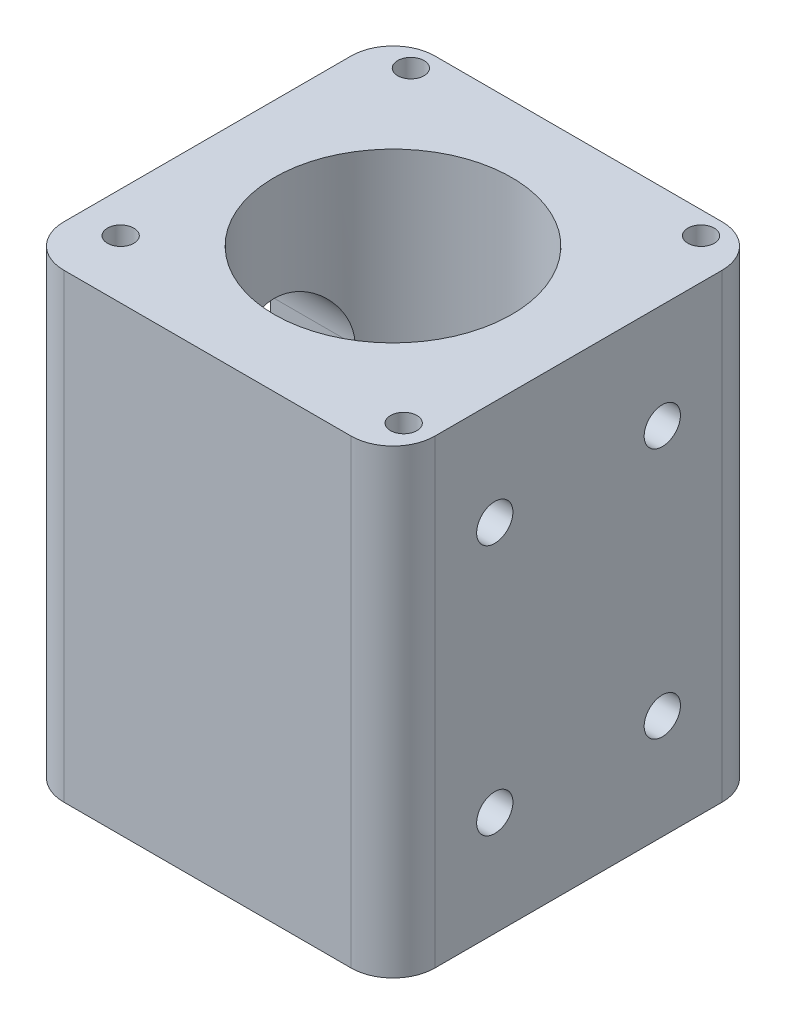
SolidWorks part; units mm, degrees
ref_plane "Front Plane" through (0, 0, 0) normal (0, 0, 1) x (1, 0, 0)
ref_plane "Top Plane" through (0, 0, 0) normal (0, 1, 0) x (1, 0, 0)
ref_plane "Right Plane" through (0, 0, 0) normal (1, 0, 0) x (0, 0, -1)
ref_plane "Plane1"
sketch "Sketch1" plane through (0, 0, 0) normal (0, 1, 0) x (-1, 0, 0)
  line L0 (28.1305, 28.1305) -> (-28.1305, 28.1305)
  line L1 (-28.1305, 28.1305) -> (-28.1305, -28.1305)
  line L2 (-28.1305, -28.1305) -> (28.1305, -28.1305)
  line L3 (28.1305, -28.1305) -> (28.1305, 28.1305)
  dimension "D1" = 56.261
  dimension "D2" = 56.261
extrude "Extrusion1" add sketch "Sketch1" along normal blind 69.85
hole_wizard "Hole1" positions "Sketch3" profile "Sketch2" legacy
sketch "Sketch3" plane through (0, 69.85, 0) normal (0, 1, 0) x (1, 0, 0)
  point P1 (-22, 24.7091)
  point P2 (22, 24.7091)
  point P3 (24.0589, -22.4333)
  point P4 (-22, -19.2909)
sketch "Sketch2" plane through (-22, 69.85, -24.7091) normal (1, 0, 0) x (0, 0, 1)
  line L0 (0, 0) -> (0, 26.6017)
  line L1 (0, 26.6017) -> (2, 25.4)
  line L2 (2, 25.4) -> (2, 0)
  line L4 (2, 0) -> (0, 0)
  line L6 (0, 26.6017) -> (-2, 25.4) construction
  line L7 (0, -4.2442) -> (0, 117.3081) construction
  dimension "Diameter" = 4
  dimension "Depth" = 25.4
  dimension "Drill Angle" = 118
sketch "Sketch4" plane through (0, 69.85, 0) normal (0, 1, 0) x (-1, 0, 0)
  circle A0 centre (0, 0) radius 18
  dimension "D1" = 36
extrude "Extrusion2" cut sketch "Sketch4" against normal blind 254
hole_wizard "Hole2" positions "Sketch6" profile "Sketch5" legacy
sketch "Sketch6" plane through (0, 0, 0) normal (0, -1, 0) x (-1, 0, 0)
  point P1 (23.3446, -23.5712)
  point P2 (-23.7978, -23.5712)
  point P3 (-23.7978, 23.5712)
  point P4 (23.3446, 23.5712)
sketch "Sketch5" plane through (-23.3446, 0, 23.5712) normal (1, 0, 0) x (0, 0, -1)
  line L0 (0, 0) -> (0, 26.9022)
  line L1 (0, 26.9022) -> (2.5, 25.4)
  line L2 (2.5, 25.4) -> (2.5, 0)
  line L4 (2.5, 0) -> (0, 0)
  line L6 (0, 26.9022) -> (-2.5, 25.4) construction
  line L7 (0, -4.2442) -> (0, 117.3081) construction
  dimension "Diameter" = 5
  dimension "Depth" = 25.4
  dimension "Drill Angle" = 118
ref_plane "Plane2"
sketch "Sketch7" plane through (0, 0, 0) normal (0, -1, 0) x (1, 0, 0)
  circle A0 centre (0, 0) radius 19.0754
  circle A1 centre (0, 0) radius 18
  dimension "D1" = 38.1508
extrude "Extrusion3" cut sketch "Sketch7" against normal blind 34.925 contours A0 A1
fillet "Fillet1" radius 6.35 1 edges at (28.1305, 34.925, 28.1305)
fillet "Fillet2" radius 6.35 1 edges at (-28.1305, 34.925, 28.1305)
fillet "Fillet3" radius 6.35 1 edges at (28.1305, 34.925, -28.1305)
fillet "Fillet4" radius 6.35 1 edges at (-28.1305, 34.925, -28.1305)
sketch "Sketch8" plane through (-28.1305, 0, 0) normal (-1, 0, 0) x (0, 0, 1)
  line L0 (-9.525, 25.4) -> (-9.525, 44.45)
  line L1 (9.525, 44.45) -> (9.525, 25.4)
  arc A0 (9.525, 44.45) -> (-9.525, 44.45) centre (0, 44.45) ccw
  arc A1 (-9.525, 25.4) -> (9.525, 25.4) centre (0, 25.4) ccw
extrude "Extrusion4" cut sketch "Sketch8" against normal blind 25.4
hole_wizard "Hole3" positions "Sketch10" profile "Sketch9" legacy
sketch "Sketch10" plane through (28.1305, 0, 0) normal (1, 0, 0) x (0, 0, -1)
  point P1 (-12.7, 53.975)
  point P2 (12.7, 53.975)
  point P3 (12.7, 15.875)
  point P4 (-12.7, 15.875)
sketch "Sketch9" plane through (28.1305, 53.975, 12.7) normal (0, 1, 0) x (0, 0, -1)
  line L0 (0, 0) -> (0, 27.0524)
  line L1 (0, 27.0524) -> (2.75, 25.4)
  line L2 (2.75, 25.4) -> (2.75, 0)
  line L4 (2.75, 0) -> (0, 0)
  line L6 (0, 27.0524) -> (-2.75, 25.4) construction
  line L7 (0, -4.2442) -> (0, 117.3081) construction
  dimension "Diameter" = 5.5
  dimension "Depth" = 25.4
  dimension "Drill Angle" = 118
